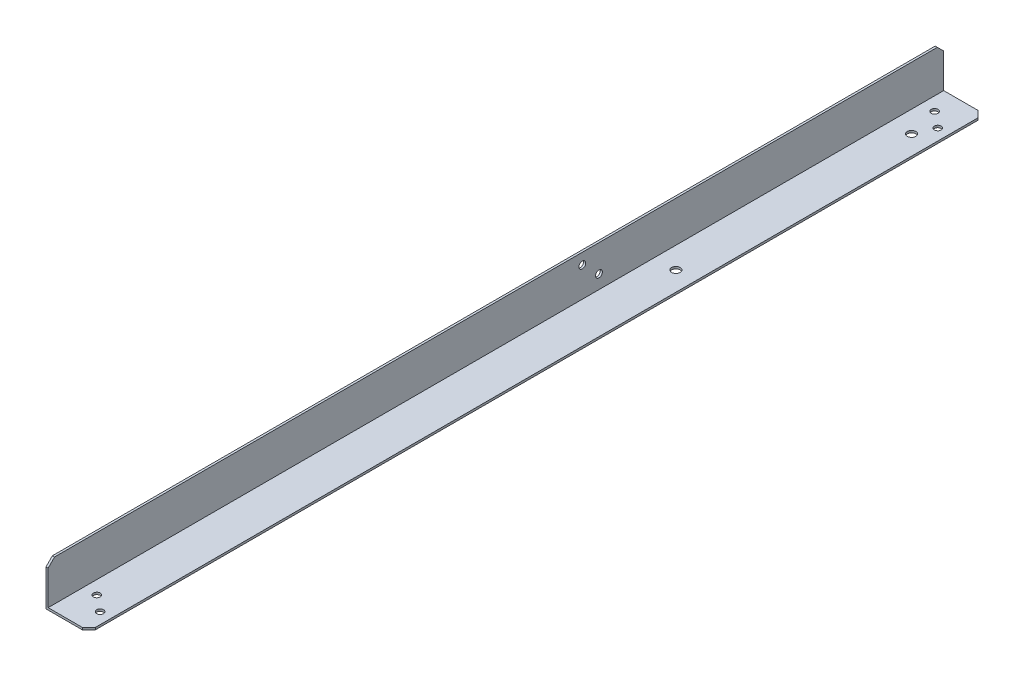
SolidWorks part; units mm, degrees
material "6063-T5"
ref_plane "Спереди" through (0, 0, 0) normal (0, 0, 1) x (1, 0, 0)
ref_plane "Сверху" through (0, 0, 0) normal (0, 1, 0) x (1, 0, 0)
ref_plane "Справа" through (0, 0, 0) normal (1, 0, 0) x (0, 0, -1)
sketch "Sketch1" plane through (0, 0, 0) normal (0, 0, 1) x (1, 0, 0)
  line L0 (0, 0) -> (20, 0)
  line L1 (20, 0) -> (20, 1)
  line L2 (20, 1) -> (1, 1)
  line L3 (1, 1) -> (1, 20)
  line L4 (1, 20) -> (0, 20)
  line L5 (0, 20) -> (0, 0)
  dimension "D1" = 20
  dimension "D2" = 20
  dimension "D4" = 1
extrude "Base" add sketch "Sketch1" along normal blind 418
chamfer "Chamfer1" distance 3 angle 45 4 edges at (20, 0.5, 418) (0.5, 20, 418) (0.5, 20, 0) (20, 0.5, 0)
hole_wizard "Ø3.2 (3.2) Cable Carrier Holes" positions "Sketch6" profile "Sketch7" hole size "Ø3.2" standard "ANSI Metric" end condition through all
sketch "Sketch6" plane through (1, 0, 0) normal (1, 0, 0) x (0, 0, -1)
  line L0 (-415, 0) -> (-3, 0) construction
  line L1 (0, 1) -> (0, 17) construction
  point P0 (-168.7, 14.85)
  point P2 (-160.9, 7.35)
  dimension "D1" = 7.5
  dimension "D2" = 7.8
  dimension "D3" = 7.35
  dimension "D4" = 168.7
sketch "Sketch7" plane through (1, 14.85, 168.7) normal (0, 1, 0) x (0, 0, -1)
  line L0 (0, 0) -> (0, 1)
  line L1 (0, 1) -> (1.6, 1)
  line L2 (1.6, 1) -> (1.6, 0)
  line L5 (1.6, 0) -> (0, 0)
  line L11 (0, -6.35) -> (0, 107.95) construction
  dimension "Thru Hole Dia." = 3.2
  dimension "Thru Hole Depth" = 1
hole_wizard "Ø3.2 (3.2) Diameter Hole2" positions "Sketch8" profile "Sketch9" hole size "Ø3.2" standard "ANSI Metric" end condition through all
sketch "Sketch8" plane through (0, 1, 0) normal (0, 1, 0) x (1, 0, 0)
  line L0 (0, -415) -> (0, -3) construction
  line L2 (17, -418) -> (1, -418) construction
  point P0 (7.25, -401.5)
  point P2 (14.75, -407.5)
  point P4 (7.25, -10.5)
  point P6 (14.75, -16.5)
  dimension "D1" = 6
  dimension "D2" = 6
  dimension "D3" = 7.5
  dimension "D4" = 7.25
  dimension "D5" = 10.5
  dimension "D6" = 391
sketch "Sketch9" plane through (7.25, 1, 401.5) normal (1, 0, 0) x (0, 0, 1)
  line L0 (0, 0) -> (0, 1)
  line L1 (0, 1) -> (1.6, 1)
  line L2 (1.6, 1) -> (1.6, 0)
  line L5 (1.6, 0) -> (0, 0)
  line L11 (0, -6.35) -> (0, 107.95) construction
  dimension "Thru Hole Dia." = 3.2
  dimension "Thru Hole Depth" = 1
hole_wizard "Ø4.0 (4) Cable Tie Holes" positions "Sketch10" profile "Sketch11" hole size "Ø4.0" standard "ANSI Metric" end condition through all
sketch "Sketch10" plane through (0, 1, 0) normal (0, 1, 0) x (1, 0, 0)
  line L0 (0, -415) -> (0, -3) construction
  line L1 (17, 0) -> (1, 0) construction
  point P0 (11, -25)
  point P2 (11, -135)
  dimension "D1" = 11
  dimension "D2" = 25
  dimension "D3" = 135
sketch "Sketch11" plane through (11, 1, 25) normal (1, 0, 0) x (0, 0, 1)
  line L0 (0, 0) -> (0, 1)
  line L1 (0, 1) -> (2, 1)
  line L2 (2, 1) -> (2, 0)
  line L5 (2, 0) -> (0, 0)
  line L11 (0, -6.35) -> (0, 107.95) construction
  dimension "Thru Hole Dia." = 4
  dimension "Thru Hole Depth" = 1
equation "\"D1@Sketch1\"=\"D2@Sketch1\""
